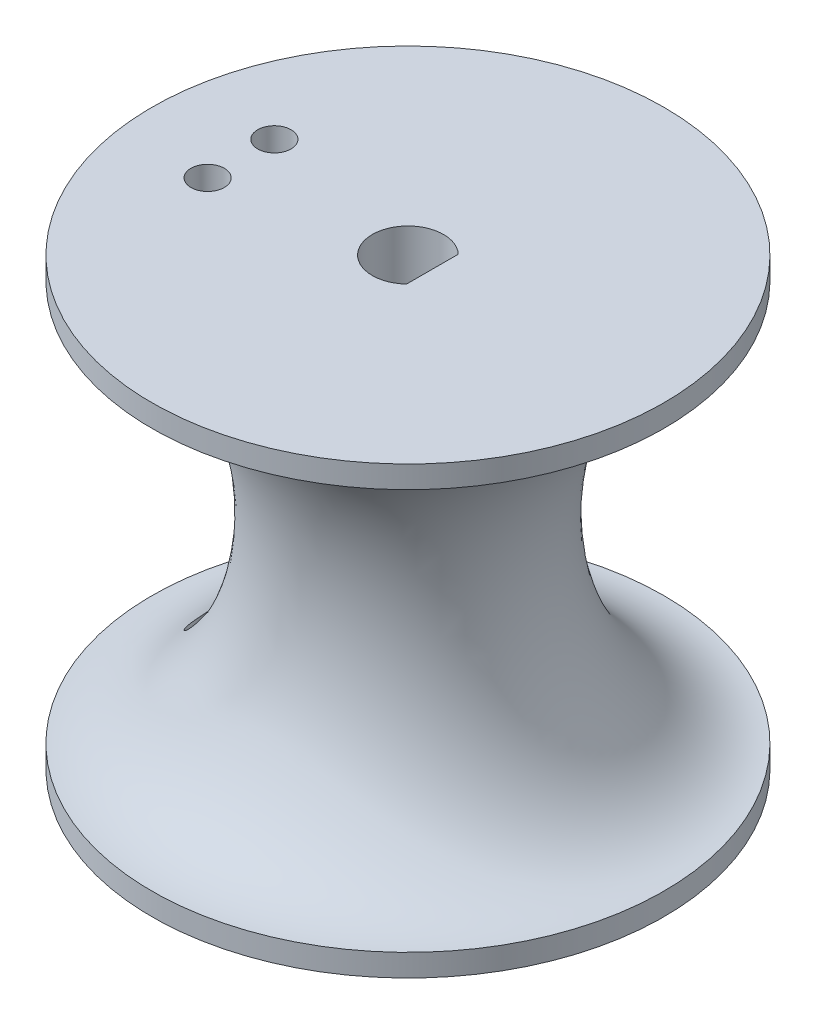
SolidWorks part; units mm, degrees
ref_plane "Front Plane" through (0, 0, 0) normal (0, 0, 1) x (1, 0, 0)
ref_plane "Top Plane" through (0, 0, 0) normal (0, 1, 0) x (1, 0, 0)
ref_plane "Right Plane" through (0, 0, 0) normal (1, 0, 0) x (0, 0, -1)
sketch "Sketch4" plane through (0, 0, 0) normal (0, 0, 1) x (1, 0, 0)
  line L11 (-23, 0) -> (0, 0)
  line L12 (0, 0) -> (0, 40)
  line L21 (-23, 0) -> (-23, 5)
  line L22 (0, 20) -> (-10, 20) construction
  line L25 (-23, 40) -> (-23, 35)
  line L26 (-23, 40) -> (0, 40)
  line L27 (-23, 5) -> (-23, 35)
  dimension "D1" = 5
  dimension "D2" = 23
ref_axis "Axis1" through (0, -1.5, 0) along (0, 1, 0)
revolve "Revolve1" add sketch "Sketch4" angle 360 about axis through (0, -1.5, 0) along (0, 1, 0)
sketch "Sketch1" plane through (0, 0, 0) normal (0, -1, 0) x (-1, 0, 0)
  line L0 (-2, 2.2361) -> (-2, -2.2361) construction
  line L1 (-2.2, 2.3238) -> (-2.2, -2.3238)
  line L2 (15, 0) -> (0, 0) construction
  arc A0 (-2, -2.2361) -> (-2, 2.2361) centre (0, 0) ccw construction
  arc A1 (-2.2, -2.3238) -> (-2.2, 2.3238) centre (0, 0) ccw
  circle A4 centre (15, 3) radius 1.5
  circle A5 centre (15, -3) radius 1.5
  dimension "D1" = 6
  dimension "D4" = 3
  dimension "D2" = 2
  dimension "D5" = 15
  dimension "D6" = 3
  dimension "D3" = 0.2
sketch "Sketch8" plane through (0, 0, 0) normal (0, 0, 1) x (1, 0, 0)
  line L0 (-23, 40) -> (-23, 0) construction
  ellipse E0 centre (-23, 20) end of major axis (-23, 38) minor radius 12
  point P1 (0, 0)
revolve "Cut-Revolve2" cut sketch "Sketch8" angle 360 about axis through (0, -1.5, 0) along (0, 1, 0)
extrude "Cut-Extrude1" cut sketch "Sketch1" against normal through all
